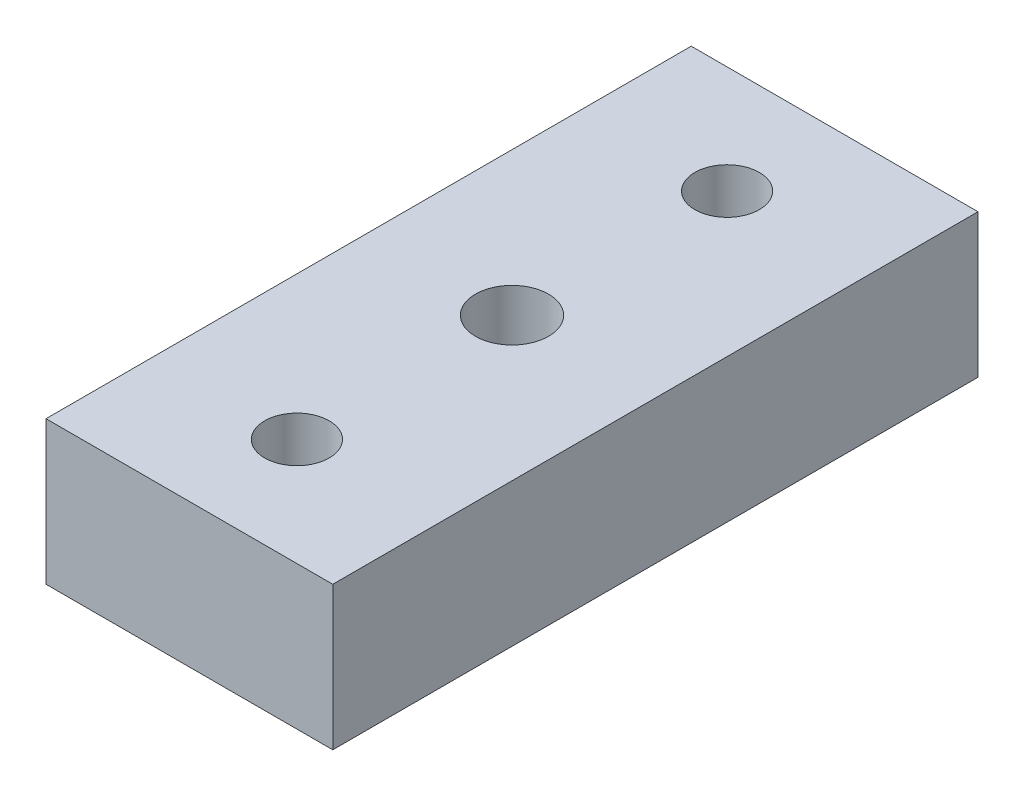
SolidWorks part; units mm, degrees
material "6061 合金"
ref_plane "前视基准面" through (0, 0, 0) normal (0, 0, 1) x (1, 0, 0)
ref_plane "上视基准面" through (0, 0, 0) normal (0, 1, 0) x (1, 0, 0)
ref_plane "右视基准面" through (0, 0, 0) normal (1, 0, 0) x (0, 0, -1)
other "Configuration Table"
sketch "Sketch1" plane through (0, 0, 0) normal (0, 1, 0) x (1, 0, 0)
  line L1 (-20, -45) -> (20, -45)
  line L2 (-20, -45) -> (-20, 45)
  line L3 (-20, 45) -> (20, 45)
  line L4 (20, -45) -> (20, 45)
extrude "Boss-Extrude1" add sketch "Sketch1" along normal blind 20
sketch "Sketch2" plane through (0, 0, 0) normal (0, 1, 0) x (1, 0, 0)
  circle A0 centre (0, 0) radius 5.1
extrude "Cut-Extrude1" cut sketch "Sketch2" against normal through all and the other way through all
sketch "Sketch3" plane through (0, 0, 0) normal (0, 1, 0) x (1, 0, 0)
  circle A0 centre (0, -30) radius 4.5
  circle A1 centre (0, 30) radius 4.5
extrude "Cut-Extrude2" cut sketch "Sketch3" against normal through all and the other way through all
sketch "Sketch4" plane through (0, 0, 0) normal (0, 1, 0) x (1, 0, 0)
  circle A0 centre (0, -30) radius 7
  circle A1 centre (0, 30) radius 7
extrude "Cut-Extrude4" cut sketch "Sketch4" along normal blind 9
